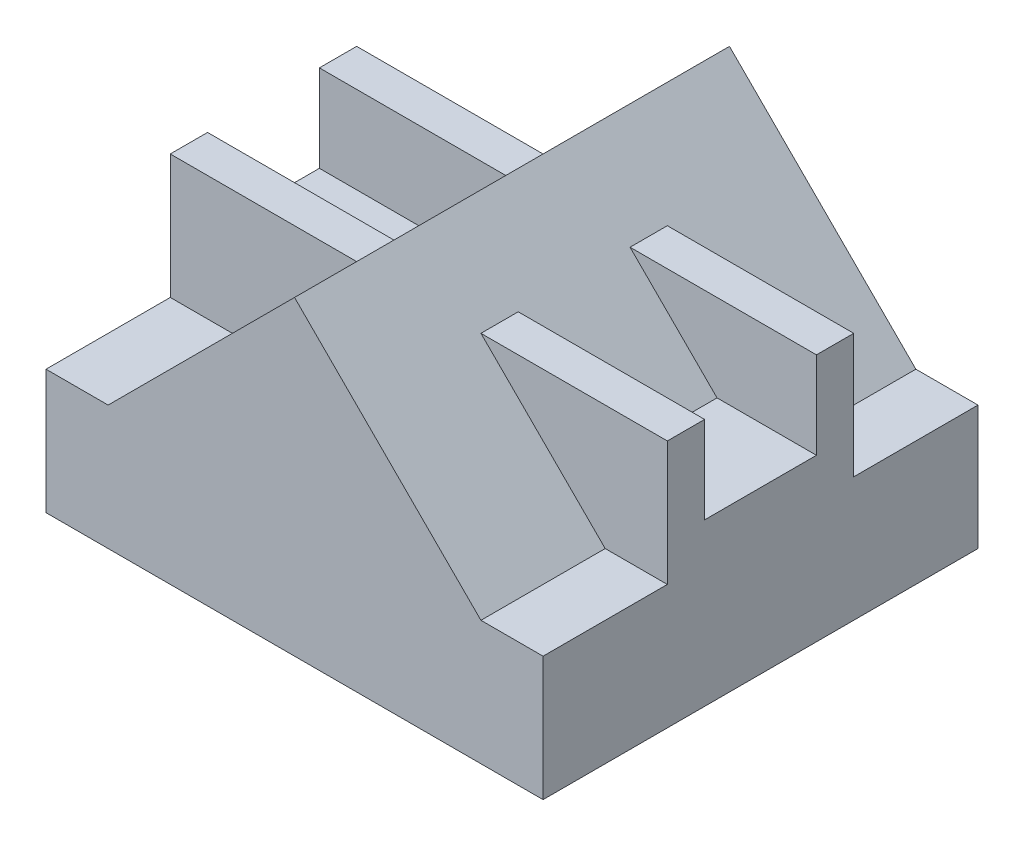
SolidWorks part; units mm, degrees
ref_plane "Płaszczyzna przednia" through (0, 0, 0) normal (0, 0, 1) x (1, 0, 0)
ref_plane "Płaszczyzna górna" through (0, 0, 0) normal (0, 1, 0) x (1, 0, 0)
ref_plane "Płaszczyzna prawa" through (0, 0, 0) normal (1, 0, 0) x (0, 0, -1)
sketch "Szkic2" plane through (0, 0, 0) normal (0, 1, 0) x (1, 0, 0)
  line L1 (-100, 87.5) -> (100, 87.5)
  line L2 (-100, 87.5) -> (-100, -87.5)
  line L3 (-100, -87.5) -> (100, -87.5)
  line L4 (100, 87.5) -> (100, -87.5)
  line L5 (-100, 87.5) -> (100, -87.5) construction
  line L6 (-100, -87.5) -> (100, 87.5) construction
  point P0 (0, 0)
  dimension "D1" = 200
  dimension "D2" = 175
extrude "Dodanie-wyciągnięcie1" add sketch "Szkic2" along normal blind 50
sketch "Szkic3" plane through (0, 0, 87.5) normal (0, 0, 1) x (1, 0, 0)
  line L0 (-75, 50) -> (0, 125)
  line L1 (-100, 50) -> (100, 50) construction
  line L2 (0, 125) -> (75, 50)
  line L3 (75, 50) -> (-75, 50)
  line L4 (0, 0) -> (0, 125) construction
  point P8 (0, 0)
  dimension "D1" = 125
extrude "Dodanie-wyciągnięcie2" add sketch "Szkic3" against normal up to surface (175 mm away) up to face at (0, 25, -87.5)
sketch "Szkic4" plane through (100, 0, 0) normal (1, 0, 0) x (0, 0, -1)
  line L0 (-37.5, 50) -> (-37.5, 100)
  line L1 (87.5, 50) -> (-87.5, 50) construction
  line L2 (-37.5, 100) -> (-22.5, 100)
  line L3 (-22.5, 100) -> (-22.5, 65)
  line L4 (-22.5, 65) -> (22.5, 65)
  line L5 (22.5, 65) -> (22.5, 100)
  line L6 (22.5, 100) -> (37.5, 100)
  line L7 (37.5, 100) -> (37.5, 50)
  line L8 (-87.5, 50) -> (87.5, 50) construction
  line L9 (37.5, 50) -> (-37.5, 50)
  line L10 (0, 0) -> (0, 65) construction
  line L12 (-87.5, 0) -> (87.5, 0) construction
  line L13 (-87.5, 50) -> (-87.5, 125) construction
  dimension "D1" = 15
  dimension "D2" = 15
  dimension "D3" = 100
  dimension "D4" = 50
extrude "Dodanie-wyciągnięcie3" add sketch "Szkic4" against normal up to surface (200 mm away) up to face at (-100, 25, 0)
